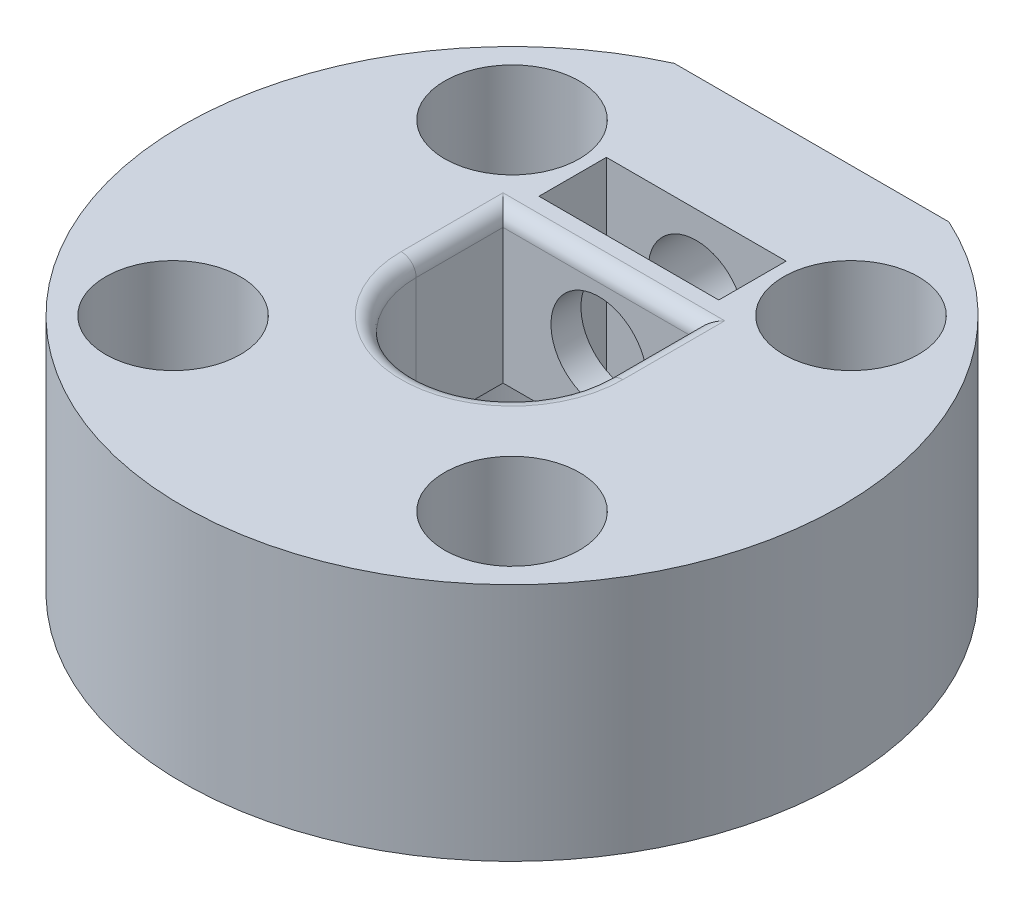
SolidWorks part; units mm, degrees
ref_plane "Plan de face" through (0, 0, 0) normal (0, 0, 1) x (1, 0, 0)
ref_plane "Plan de dessus" through (0, 0, 0) normal (0, 1, 0) x (1, 0, 0)
ref_plane "Plan de droite" through (0, 0, 0) normal (1, 0, 0) x (0, 0, -1)
sketch "Esquisse1" plane through (0, 0, 0) normal (0, 1, 0) x (1, 0, 0)
  line L1 (-3.2, 0) -> (-3.2, 2.9)
  line L2 (3.2, 0) -> (3.2, 2.9)
  line L3 (3.2, 2.9) -> (-3.2, 2.9)
  line L4 (4.5826, 10) -> (-4.5826, 10)
  arc A0 (-4.5826, 10) -> (4.5826, 10) centre (0, 0) ccw
  arc A1 (-3.2, 0) -> (3.2, 0) centre (0, 0) ccw
  point P10 (0, 2.9)
  dimension "D1" = 22
  dimension "D2" = 6.4
  dimension "D3" = 2.9
  dimension "D4" = 10
extrude "Boss.-Extru.1" add sketch "Esquisse1" along normal blind 8
hole_wizard "Chambrage pour vis à tête cylindrique à 6 pans creux (ou vis CHC) M21" positions "Esquisse2" profile "Esquisse3" counterbore size "M2" standard "Ansi Metric" end condition through all
sketch "Esquisse2" plane through (0, 8, 0) normal (0, 1, 0) x (1, 0, 0)
  line L0 (0, 0) -> (6.1221, 0) construction
  line L2 (0, 0) -> (9.471, 9.471) construction
  point P0 (5.6569, 5.6569)
  point P28 (5.6569, -5.6569)
  point P29 (-5.6569, -5.6569)
  point P30 (-5.6569, 5.6569)
  point P31 (0, 0)
  dimension "D1" = 8
  dimension "D3" = 45
  dimension "D2" = 4
sketch "Esquisse3" plane through (5.6569, 8, -5.6569) normal (1, 0, 0) x (0, 0, 1)
  line L0 (0, 0) -> (0, 8)
  line L1 (0, 8) -> (1.25, 8)
  line L3 (1.25, 8) -> (1.25, 6.5)
  line L4 (1.25, 6.5) -> (2.25, 6.5)
  line L5 (2.25, 6.5) -> (2.25, 0)
  line L7 (2.25, 0) -> (0, 0)
  line L11 (0, -6.35) -> (0, 107.95) construction
  dimension "Diamètre du perçage jusqu'au prochain" = 2.5
  dimension "Profondeur du perçage jusqu'au prochain" = 8
  dimension "Diamètre du chambrage" = 4.5
  dimension "Profondeur du chambrage" = 6.5
fillet "Congé1" radius 0.5 4 edges at (0, 8, 3.2) (-3.2, 8, -1.45) (3.2, 8, -1.45) (0, 8, -2.9)
sketch "Esquisse6" plane through (0, 0, 0) normal (0, 0, 1) x (1, 0, 0)
  line L0 (0, 0) -> (0, 8) construction
  line L1 (11, 8) -> (-11, 8) construction
  line L2 (11, 8) -> (-11, 8) construction
  circle A0 centre (0, 5.5) radius 1.6
  dimension "D1" = 3.2
  dimension "D2" = 2.5
extrude "Enlèv. mat.-Extru.1" cut sketch "Esquisse6" against normal through all
sketch "Esquisse7" plane through (0, 8, 0) normal (0, 1, 0) x (1, 0, 0)
  line L1 (-3, 3.9) -> (3, 3.9)
  line L2 (-3, 3.9) -> (-3, 6.15)
  line L3 (-3, 6.15) -> (3, 6.15)
  line L4 (3, 3.9) -> (3, 6.15)
  line L5 (-3, 3.9) -> (3, 6.15) construction
  line L6 (-3, 6.15) -> (3, 3.9) construction
  line L7 (3.2, 2.9) -> (-3.2, 2.9) construction
  point P0 (0, 5.025)
  dimension "D3" = 1
  dimension "D1" = 2.25
  dimension "D2" = 6
extrude "Enlèv. mat.-Extru.2" cut sketch "Esquisse7" against normal through all
sketch "Esquisse8" plane through (0, 0, 0) normal (0, -1, 0) x (-1, 0, 0)
  circle A0 centre (0, 0) radius 5.5
  dimension "D1" = 11
extrude "Enlèv. mat.-Extru.3" cut sketch "Esquisse8" against normal blind 3
